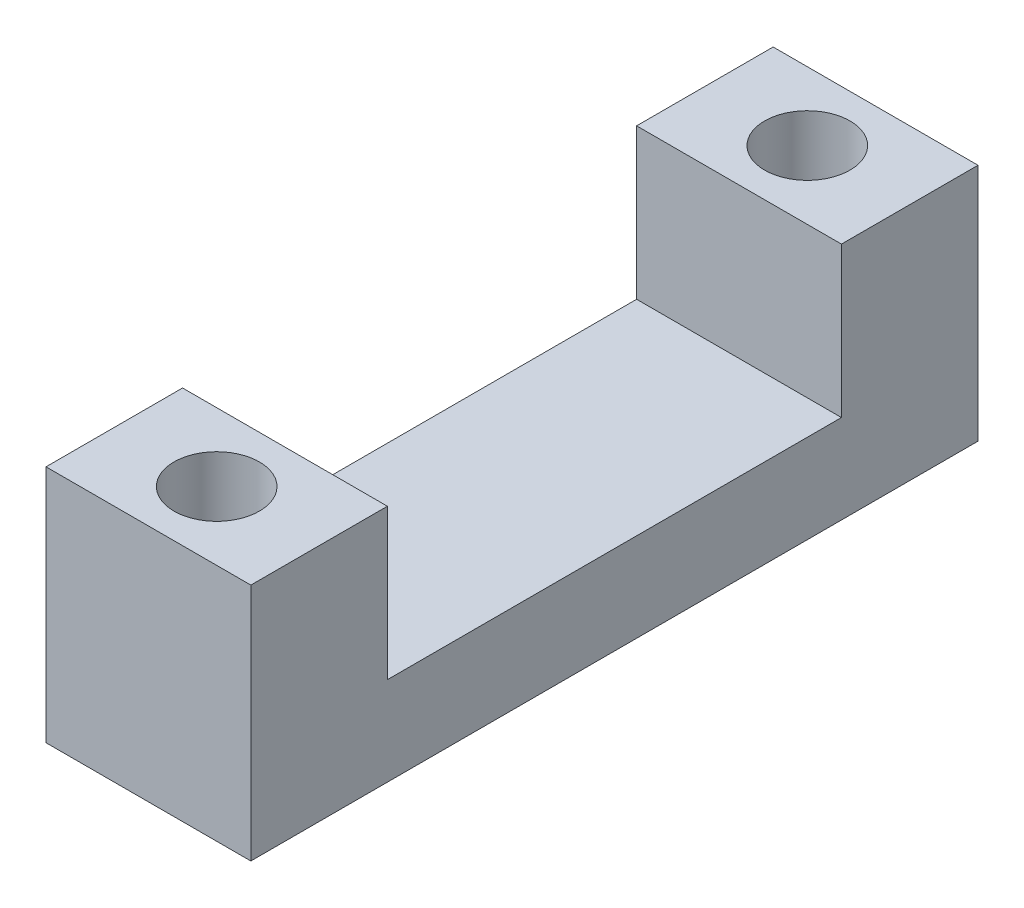
SolidWorks part; units mm, degrees
material "AISI 类型 A2 刀具钢"
ref_plane "前视基准面" through (0, 0, 0) normal (0, 0, 1) x (1, 0, 0)
ref_plane "上视基准面" through (0, 0, 0) normal (0, 1, 0) x (1, 0, 0)
ref_plane "右视基准面" through (0, 0, 0) normal (1, 0, 0) x (0, 0, -1)
sketch "草图1" plane through (0, 0, 0) normal (1, 0, 0) x (0, 0, -1)
  line L0 (0, 0) -> (0, 7)
  line L1 (0, 7) -> (4, 7)
  line L2 (4, 7) -> (4, 2.6)
  line L3 (4, 2.6) -> (17.3, 2.6)
  line L4 (17.3, 2.6) -> (17.3, 7)
  line L5 (17.3, 7) -> (21.3, 7)
  line L6 (21.3, 7) -> (21.3, 0)
  line L7 (21.3, 0) -> (0, 0)
  line L8 (10.65, 0) -> (10.65, 2.6) construction
  dimension "D1" = 13.3
  dimension "D2" = 4.4
  dimension "D3" = 4
  dimension "D4" = 2.6
extrude "凸台-拉伸1" add sketch "草图1" along normal blind 6
sketch "草图2" plane through (0, 7, 0) normal (0, 1, 0) x (1, 0, 0)
  line L0 (3, 0) -> (3, 21.3) construction
  line L3 (6, 0) -> (0, 0) construction
  line L4 (6, 21.3) -> (0, 21.3) construction
  point P6 (3, 19.3)
  point P7 (3, 2)
  dimension "D2" = 2
  dimension "D1" = 2
hole_wizard "M3 螺纹孔1" positions "3D草图1" profile "草图3" tap size "M3" standard "GB" end condition through all
sketch3d "3D草图1"
  point P0 (3, 7, -2)
  point P4 (3, 7, -19.3)
sketch "草图3" plane through (3, 7, -2) normal (1, 0, 0) x (0, 0, 1)
  line L0 (0, 0) -> (0, 7)
  line L1 (0, 7) -> (1.25, 7)
  line L2 (1.25, 7) -> (1.25, 0)
  line L5 (1.25, 0) -> (0, 0)
  line L11 (0, -6.35) -> (0, 107.95) construction
  dimension "通孔螺纹孔钻头直径" = 2.5
  dimension "通孔螺纹孔钻头深度" = 7
cosmetic thread "孔螺蚊线1"
cosmetic thread "孔螺蚊线2"
